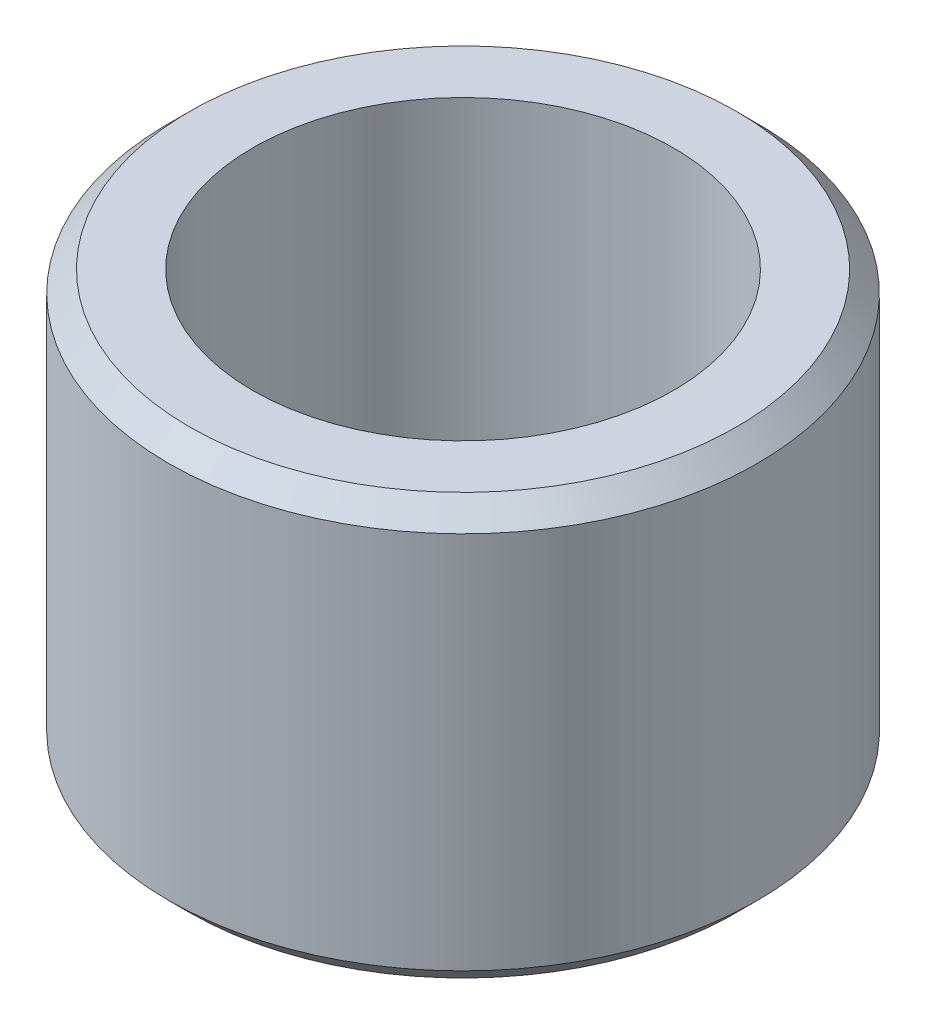
SolidWorks part; units mm, degrees
ref_plane "前视基准面" through (0, 0, 0) normal (0, 0, 1) x (1, 0, 0)
ref_plane "上视基准面" through (0, 0, 0) normal (0, 1, 0) x (1, 0, 0)
ref_plane "右视基准面" through (0, 0, 0) normal (1, 0, 0) x (0, 0, -1)
sketch "草图1" plane through (0, 0, 0) normal (0, 1, 0) x (1, 0, 0)
  circle A0 centre (0, 0) radius 7
  circle A1 centre (0, 0) radius 5
  dimension "D1" = 14
  dimension "D2" = 10
extrude "凸台-拉伸1" add sketch "草图1" along normal mid plane 10
chamfer "倒角1" distance 0.5 angle 45 2 edges at (0, -5, 7) (0, 5, 7)
